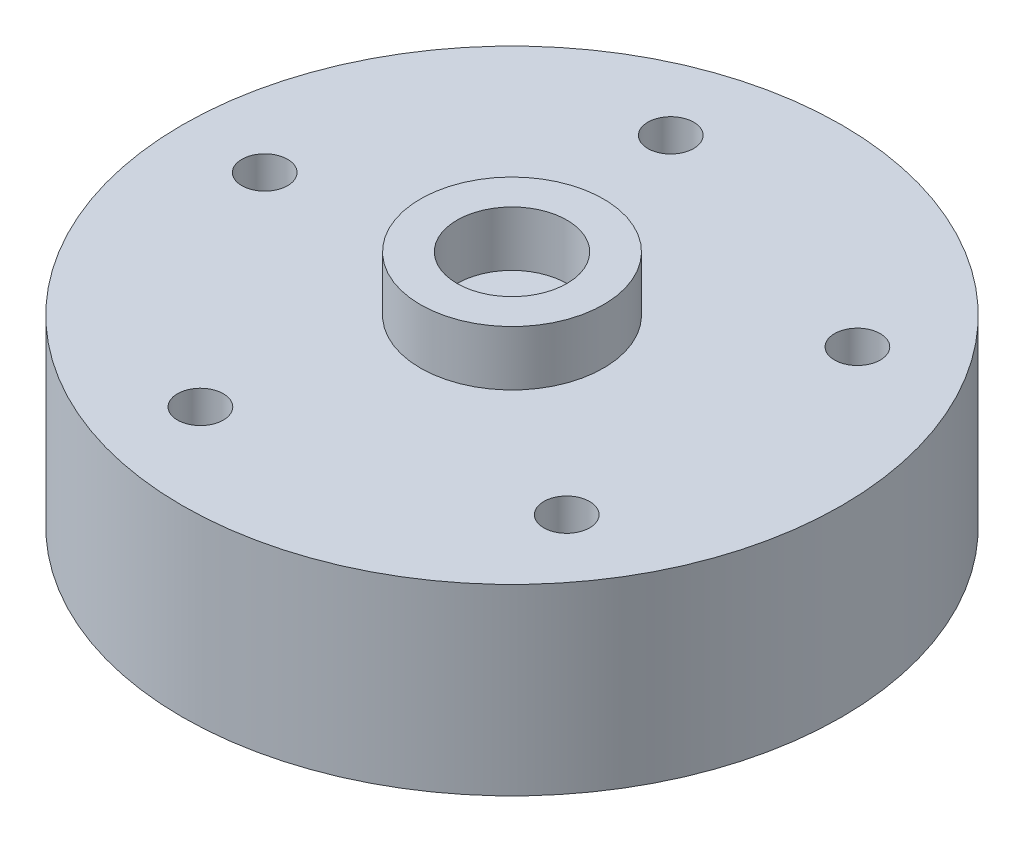
SolidWorks part; units mm, degrees
ref_plane "Front Plane" through (0, 0, 0) normal (0, 0, 1) x (1, 0, 0)
ref_plane "Top Plane" through (0, 0, 0) normal (0, 1, 0) x (1, 0, 0)
ref_plane "Right Plane" through (0, 0, 0) normal (1, 0, 0) x (0, 0, -1)
sketch "Sketch1" plane through (0, 0, 0) normal (0, 1, 0) x (1, 0, 0)
  line L0 (-13.5, 0) -> (13.5, 0) construction
  circle A0 centre (0, 0) radius 16
  circle A1 centre (0, 0) radius 13.5
  circle A2 centre (0, 0) radius 1.25
  circle A3 centre (-13.5, 0) radius 1.25
  circle A4 centre (-4.1717, 12.8393) radius 1.25
  circle A5 centre (10.9217, 7.9351) radius 1.25
  circle A6 centre (10.9217, -7.9351) radius 1.25
  circle A7 centre (-4.1717, -12.8393) radius 1.25
  point P19 (0, 0)
  dimension "D1" = 32
  dimension "D2" = 2.5
  dimension "D3" = 2.5
  dimension "D4" = 2.5
  dimension "D5" = 5
extrude "Boss-Extrude1" add sketch "Sketch1" along normal blind 2 and the other way blind 3 contours A0 A7 A1 A3 A4 A5 A6 | L0 A3 A1 A7 A6 A2 | A3 L0 A2 A1 A5 A4
sketch "Sketch2" plane through (0, 2, 0) normal (0, 1, 0) x (1, 0, 0)
  circle A0 centre (0, 0) radius 3
  circle A1 centre (0, 0) radius 5
  dimension "D1" = 6
  dimension "D2" = 2
extrude "Boss-Extrude3" add sketch "Sketch2" along normal blind 3 contours A1 A0
sketch "Sketch4" plane through (0, 2, 0) normal (0, 1, 0) x (1, 0, 0)
  circle A0 centre (0, 0) radius 2
sketch "Sketch5" plane through (0, -3, 0) normal (0, -1, 0) x (1, 0, 0)
  circle A0 centre (0, 0) radius 2.75
  dimension "D1" = 5.5
extrude "Cut-Extrude2" cut sketch "Sketch5" against normal blind 1
sketch "Sketch6" plane through (0, -3, 0) normal (0, -1, 0) x (1, 0, 0)
  circle A0 centre (0, 0) radius 16
  circle A1 centre (0, 0) radius 11
  circle A2 centre (0, 0) radius 16 construction
  circle A3 centre (-13.5, 0) radius 1.25
  circle A4 centre (-4.1717, 12.8393) radius 1.25
  circle A5 centre (10.9217, 7.9351) radius 1.25
  circle A6 centre (10.9217, -7.9351) radius 1.25
  circle A7 centre (-4.1717, -12.8393) radius 1.25
  point P20 (0, 0)
  dimension "D1" = 5
  dimension "D3" = 2.5
  dimension "D2" = 5
extrude "Boss-Extrude4" add sketch "Sketch6" along normal blind 5
sketch "Sketch7" plane through (0, 2, 0) normal (0, 1, 0) x (1, 0, 0)
  circle A0 centre (0, 0) radius 16
  circle A1 centre (0, 0) radius 18
  dimension "D1" = 2
extrude "Boss-Extrude5" add sketch "Sketch7" against normal blind 10
sketch "Sketch8" plane through (0, -2, 0) normal (0, -1, 0) x (1, 0, 0)
  circle A0 centre (0, 0) radius 2
extrude "Cut-Extrude3" cut sketch "Sketch8" against normal blind 3
sketch "Sketch9" plane through (0, -3, 0) normal (0, -1, 0) x (1, 0, 0)
  circle A0 centre (0, 0) radius 3.75
  dimension "D1" = 7.5
extrude "Cut-Extrude4" cut sketch "Sketch9" against normal blind 2
